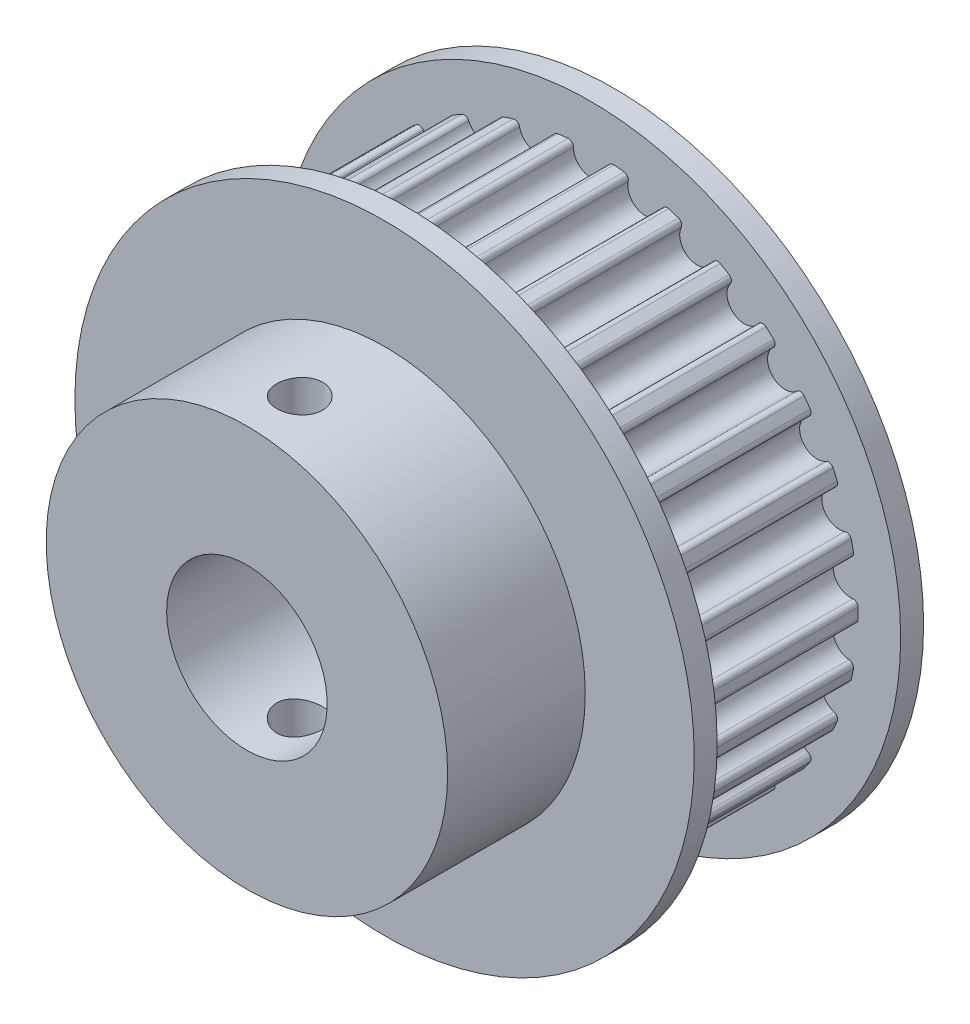
SolidWorks part; units mm, degrees
ref_plane "Front Plane" through (0, 0, 0) normal (0, 0, 1) x (1, 0, 0)
ref_plane "Top Plane" through (0, 0, 0) normal (0, 1, 0) x (1, 0, 0)
ref_plane "Right Plane" through (0, 0, 0) normal (1, 0, 0) x (0, 0, -1)
sketch "Sketch1" plane through (0, 0, 0) normal (0, 0, 1) x (1, 0, 0)
  line L0 (0, 0) -> (0, 28.7354) construction
  line L1 (0, 0) -> (41.8889, 0) construction
  line L2 (4.416, 20.7759) -> (6.2544, 29.4245) construction
  arc A2 (0, 21.24) -> (1.5249, 22.7816) centre (0, 22.765) ccw
  arc A4 (1.9916, 23.2147) -> (1.5249, 22.7816) centre (1.9549, 22.7863) ccw
  arc A5 (3.245, 22.6008) -> (4.416, 20.7759) centre (4.7331, 22.2675) ccw
  arc A6 (3.245, 22.6008) -> (2.8785, 23.1215) centre (2.8254, 22.6948) ccw
  arc A7 (2.8785, 23.1215) -> (1.9916, 23.2147) centre (0, 0) ccw
  arc A8 (4.416, 20.7759) -> (6.2282, 21.9667) centre (4.7331, 22.2675) ccw
  arc A9 (6.7747, 22.2933) -> (6.2282, 21.9667) centre (6.6497, 21.8819) ccw
  arc A10 (7.6228, 22.0178) -> (6.7747, 22.2933) centre (0, 0) ccw
  arc A11 (7.873, 21.4323) -> (7.6228, 22.0178) centre (7.4821, 21.6114) ccw
  arc A12 (7.873, 21.4323) -> (8.6391, 19.4037) centre (9.2594, 20.7969) ccw
  arc A13 (8.6391, 19.4037) -> (10.6592, 20.1918) centre (9.2594, 20.7969) ccw
  arc A14 (11.2617, 20.3976) -> (10.6592, 20.1918) centre (11.0539, 20.0212) ccw
  arc A15 (12.034, 19.9518) -> (11.2617, 20.3976) centre (0, 0) ccw
  arc A16 (12.157, 19.327) -> (12.034, 19.9518) centre (11.8119, 19.5836) ccw
  arc A17 (12.157, 19.327) -> (12.4846, 17.1835) centre (13.3809, 18.4173) ccw
  arc A18 (12.4846, 17.1835) -> (14.6244, 17.5344) centre (13.3809, 18.4173) ccw
  arc A19 (15.2565, 17.6104) -> (14.6244, 17.5344) centre (14.975, 17.2854) ccw
  arc A20 (15.9192, 17.0138) -> (15.2565, 17.6104) centre (0, 0) ccw
  arc A21 (15.9097, 16.3771) -> (15.9192, 17.0138) centre (15.6254, 16.6998) ccw
  arc A22 (15.9097, 16.3771) -> (15.7844, 14.2123) centre (16.9177, 15.2328) ccw
  arc A23 (15.7844, 14.2123) -> (17.9504, 14.1106) centre (16.9177, 15.2328) ccw
  arc A24 (18.5846, 14.0536) -> (17.9504, 14.1106) centre (18.2416, 13.7942) ccw
  arc A25 (19.1087, 13.3322) -> (18.5846, 14.0536) centre (0, 0) ccw
  arc A26 (18.967, 12.7114) -> (19.1087, 13.3322) centre (18.7561, 13.0861) ccw
  arc A27 (18.967, 12.7114) -> (18.3944, 10.62) centre (19.7151, 11.3825) ccw
  arc A28 (18.3944, 10.62) -> (20.4919, 10.0702) centre (19.7151, 11.3825) ccw
  arc A29 (21.1004, 9.8826) -> (20.4919, 10.0702) centre (20.711, 9.7002) ccw
  arc A30 (21.4631, 9.0679) -> (21.1004, 9.8826) centre (0, 0) ccw
  arc A31 (21.1954, 8.4902) -> (21.4631, 9.0679) centre (21.067, 8.9006) ccw
  arc A32 (21.1954, 8.4902) -> (20.2004, 6.5635) centre (21.6508, 7.0348) ccw
  arc A33 (20.2004, 6.5635) -> (22.1378, 5.5896) centre (21.6508, 7.0348) ccw
  arc A34 (22.694, 5.2796) -> (22.1378, 5.5896) centre (22.2751, 5.1821) ccw
  arc A35 (22.8794, 4.4073) -> (22.694, 5.2796) centre (0, 0) ccw
  arc A36 (22.4974, 3.8979) -> (22.8794, 4.4073) centre (22.4571, 4.326) ccw
  arc A37 (22.4974, 3.8979) -> (21.1236, 2.2202) centre (22.6403, 2.3796) ccw
  arc A38 (21.1236, 2.2202) -> (22.8162, 0.8648) centre (22.6403, 2.3796) ccw
  arc A39 (23.2957, 0.4459) -> (22.8162, 0.8648) centre (22.8658, 0.4376) ccw
  arc A40 (23.2957, -0.4459) -> (23.2957, 0.4459) centre (0, 0) ccw
  arc A41 (22.8162, -0.8648) -> (23.2957, -0.4459) centre (22.8658, -0.4376) ccw
  arc A42 (22.8162, -0.8648) -> (21.1236, -2.2202) centre (22.6403, -2.3796) ccw
  arc A43 (21.1236, -2.2202) -> (22.4974, -3.8979) centre (22.6403, -2.3796) ccw
  arc A44 (22.8794, -4.4073) -> (22.4974, -3.8979) centre (22.4571, -4.326) ccw
  arc A45 (22.694, -5.2796) -> (22.8794, -4.4073) centre (0, 0) ccw
  arc A46 (22.1378, -5.5896) -> (22.694, -5.2796) centre (22.2751, -5.1821) ccw
  arc A47 (22.1378, -5.5896) -> (20.2004, -6.5635) centre (21.6508, -7.0348) ccw
  arc A48 (20.2004, -6.5635) -> (21.1954, -8.4902) centre (21.6508, -7.0348) ccw
  arc A49 (21.4631, -9.0679) -> (21.1954, -8.4902) centre (21.067, -8.9006) ccw
  arc A50 (21.1004, -9.8826) -> (21.4631, -9.0679) centre (0, 0) ccw
  arc A51 (20.4919, -10.0702) -> (21.1004, -9.8826) centre (20.711, -9.7002) ccw
  arc A52 (20.4919, -10.0702) -> (18.3944, -10.62) centre (19.7151, -11.3825) ccw
  arc A53 (18.3944, -10.62) -> (18.967, -12.7114) centre (19.7151, -11.3825) ccw
  arc A54 (19.1087, -13.3322) -> (18.967, -12.7114) centre (18.7561, -13.0861) ccw
  arc A55 (18.5846, -14.0536) -> (19.1087, -13.3322) centre (0, 0) ccw
  arc A56 (17.9504, -14.1106) -> (18.5846, -14.0536) centre (18.2416, -13.7942) ccw
  arc A57 (17.9504, -14.1106) -> (15.7844, -14.2123) centre (16.9177, -15.2328) ccw
  arc A58 (15.7844, -14.2123) -> (15.9097, -16.3771) centre (16.9177, -15.2328) ccw
  arc A59 (15.9192, -17.0138) -> (15.9097, -16.3771) centre (15.6254, -16.6998) ccw
  arc A60 (15.2565, -17.6104) -> (15.9192, -17.0138) centre (0, 0) ccw
  arc A61 (14.6244, -17.5344) -> (15.2565, -17.6104) centre (14.975, -17.2854) ccw
  arc A62 (14.6244, -17.5344) -> (12.4846, -17.1835) centre (13.3809, -18.4173) ccw
  arc A63 (12.4846, -17.1835) -> (12.157, -19.327) centre (13.3809, -18.4173) ccw
  arc A64 (12.034, -19.9518) -> (12.157, -19.327) centre (11.8119, -19.5836) ccw
  arc A65 (11.2617, -20.3976) -> (12.034, -19.9518) centre (0, 0) ccw
  arc A66 (10.6592, -20.1918) -> (11.2617, -20.3976) centre (11.0539, -20.0212) ccw
  arc A67 (10.6592, -20.1918) -> (8.6391, -19.4037) centre (9.2594, -20.7969) ccw
  arc A68 (8.6391, -19.4037) -> (7.873, -21.4323) centre (9.2594, -20.7969) ccw
  arc A69 (7.6228, -22.0178) -> (7.873, -21.4323) centre (7.4821, -21.6114) ccw
  arc A70 (6.7747, -22.2933) -> (7.6228, -22.0178) centre (0, 0) ccw
  arc A71 (6.2282, -21.9667) -> (6.7747, -22.2933) centre (6.6497, -21.8819) ccw
  arc A72 (6.2282, -21.9667) -> (4.416, -20.7759) centre (4.7331, -22.2675) ccw
  arc A73 (4.416, -20.7759) -> (3.245, -22.6008) centre (4.7331, -22.2675) ccw
  arc A74 (2.8785, -23.1215) -> (3.245, -22.6008) centre (2.8254, -22.6948) ccw
  arc A75 (1.9916, -23.2147) -> (2.8785, -23.1215) centre (0, 0) ccw
  arc A76 (1.5249, -22.7816) -> (1.9916, -23.2147) centre (1.9549, -22.7863) ccw
  arc A77 (1.5249, -22.7816) -> (0, -21.24) centre (0, -22.765) ccw
  arc A78 (0, -21.24) -> (-1.5249, -22.7816) centre (0, -22.765) ccw
  arc A79 (-1.9916, -23.2147) -> (-1.5249, -22.7816) centre (-1.9549, -22.7863) ccw
  arc A80 (-2.8785, -23.1215) -> (-1.9916, -23.2147) centre (0, 0) ccw
  arc A81 (-3.245, -22.6008) -> (-2.8785, -23.1215) centre (-2.8254, -22.6948) ccw
  arc A82 (-3.245, -22.6008) -> (-4.416, -20.7759) centre (-4.7331, -22.2675) ccw
  arc A83 (-4.416, -20.7759) -> (-6.2282, -21.9667) centre (-4.7331, -22.2675) ccw
  arc A84 (-6.7747, -22.2933) -> (-6.2282, -21.9667) centre (-6.6497, -21.8819) ccw
  arc A85 (-7.6228, -22.0178) -> (-6.7747, -22.2933) centre (0, 0) ccw
  arc A86 (-7.873, -21.4323) -> (-7.6228, -22.0178) centre (-7.4821, -21.6114) ccw
  arc A87 (-7.873, -21.4323) -> (-8.6391, -19.4037) centre (-9.2594, -20.7969) ccw
  arc A88 (-8.6391, -19.4037) -> (-10.6592, -20.1918) centre (-9.2594, -20.7969) ccw
  arc A89 (-11.2617, -20.3976) -> (-10.6592, -20.1918) centre (-11.0539, -20.0212) ccw
  arc A90 (-12.034, -19.9518) -> (-11.2617, -20.3976) centre (0, 0) ccw
  arc A91 (-12.157, -19.327) -> (-12.034, -19.9518) centre (-11.8119, -19.5836) ccw
  arc A92 (-12.157, -19.327) -> (-12.4846, -17.1835) centre (-13.3809, -18.4173) ccw
  arc A93 (-12.4846, -17.1835) -> (-14.6244, -17.5344) centre (-13.3809, -18.4173) ccw
  arc A94 (-15.2565, -17.6104) -> (-14.6244, -17.5344) centre (-14.975, -17.2854) ccw
  arc A95 (-15.9192, -17.0138) -> (-15.2565, -17.6104) centre (0, 0) ccw
  arc A96 (-15.9097, -16.3771) -> (-15.9192, -17.0138) centre (-15.6254, -16.6998) ccw
  arc A97 (-15.9097, -16.3771) -> (-15.7844, -14.2123) centre (-16.9177, -15.2328) ccw
  arc A98 (-15.7844, -14.2123) -> (-17.9504, -14.1106) centre (-16.9177, -15.2328) ccw
  arc A99 (-18.5846, -14.0536) -> (-17.9504, -14.1106) centre (-18.2416, -13.7942) ccw
  arc A100 (-19.1087, -13.3322) -> (-18.5846, -14.0536) centre (0, 0) ccw
  arc A101 (-18.967, -12.7114) -> (-19.1087, -13.3322) centre (-18.7561, -13.0861) ccw
  arc A102 (-18.967, -12.7114) -> (-18.3944, -10.62) centre (-19.7151, -11.3825) ccw
  arc A103 (-18.3944, -10.62) -> (-20.4919, -10.0702) centre (-19.7151, -11.3825) ccw
  arc A104 (-21.1004, -9.8826) -> (-20.4919, -10.0702) centre (-20.711, -9.7002) ccw
  arc A105 (-21.4631, -9.0679) -> (-21.1004, -9.8826) centre (0, 0) ccw
  arc A106 (-21.1954, -8.4902) -> (-21.4631, -9.0679) centre (-21.067, -8.9006) ccw
  arc A107 (-21.1954, -8.4902) -> (-20.2004, -6.5635) centre (-21.6508, -7.0348) ccw
  arc A108 (-20.2004, -6.5635) -> (-22.1378, -5.5896) centre (-21.6508, -7.0348) ccw
  arc A109 (-22.694, -5.2796) -> (-22.1378, -5.5896) centre (-22.2751, -5.1821) ccw
  arc A110 (-22.8794, -4.4073) -> (-22.694, -5.2796) centre (0, 0) ccw
  arc A111 (-22.4974, -3.8979) -> (-22.8794, -4.4073) centre (-22.4571, -4.326) ccw
  arc A112 (-22.4974, -3.8979) -> (-21.1236, -2.2202) centre (-22.6403, -2.3796) ccw
  arc A113 (-21.1236, -2.2202) -> (-22.8162, -0.8648) centre (-22.6403, -2.3796) ccw
  arc A114 (-23.2957, -0.4459) -> (-22.8162, -0.8648) centre (-22.8658, -0.4376) ccw
  arc A115 (-23.2957, 0.4459) -> (-23.2957, -0.4459) centre (0, 0) ccw
  arc A116 (-22.8162, 0.8648) -> (-23.2957, 0.4459) centre (-22.8658, 0.4376) ccw
  arc A117 (-22.8162, 0.8648) -> (-21.1236, 2.2202) centre (-22.6403, 2.3796) ccw
  arc A118 (-21.1236, 2.2202) -> (-22.4974, 3.8979) centre (-22.6403, 2.3796) ccw
  arc A119 (-22.8794, 4.4073) -> (-22.4974, 3.8979) centre (-22.4571, 4.326) ccw
  arc A120 (-22.694, 5.2796) -> (-22.8794, 4.4073) centre (0, 0) ccw
  arc A121 (-22.1378, 5.5896) -> (-22.694, 5.2796) centre (-22.2751, 5.1821) ccw
  arc A122 (-22.1378, 5.5896) -> (-20.2004, 6.5635) centre (-21.6508, 7.0348) ccw
  arc A123 (-20.2004, 6.5635) -> (-21.1954, 8.4902) centre (-21.6508, 7.0348) ccw
  arc A124 (-21.4631, 9.0679) -> (-21.1954, 8.4902) centre (-21.067, 8.9006) ccw
  arc A125 (-21.1004, 9.8826) -> (-21.4631, 9.0679) centre (0, 0) ccw
  arc A126 (-20.4919, 10.0702) -> (-21.1004, 9.8826) centre (-20.711, 9.7002) ccw
  arc A127 (-20.4919, 10.0702) -> (-18.3944, 10.62) centre (-19.7151, 11.3825) ccw
  arc A128 (-18.3944, 10.62) -> (-18.967, 12.7114) centre (-19.7151, 11.3825) ccw
  arc A129 (-19.1087, 13.3322) -> (-18.967, 12.7114) centre (-18.7561, 13.0861) ccw
  arc A130 (-18.5846, 14.0536) -> (-19.1087, 13.3322) centre (0, 0) ccw
  arc A131 (-17.9504, 14.1106) -> (-18.5846, 14.0536) centre (-18.2416, 13.7942) ccw
  arc A132 (-17.9504, 14.1106) -> (-15.7844, 14.2123) centre (-16.9177, 15.2328) ccw
  arc A133 (-15.7844, 14.2123) -> (-15.9097, 16.3771) centre (-16.9177, 15.2328) ccw
  arc A134 (-15.9192, 17.0138) -> (-15.9097, 16.3771) centre (-15.6254, 16.6998) ccw
  arc A135 (-15.2565, 17.6104) -> (-15.9192, 17.0138) centre (0, 0) ccw
  arc A136 (-14.6244, 17.5344) -> (-15.2565, 17.6104) centre (-14.975, 17.2854) ccw
  arc A137 (-14.6244, 17.5344) -> (-12.4846, 17.1835) centre (-13.3809, 18.4173) ccw
  arc A138 (-12.4846, 17.1835) -> (-12.157, 19.327) centre (-13.3809, 18.4173) ccw
  arc A139 (-12.034, 19.9518) -> (-12.157, 19.327) centre (-11.8119, 19.5836) ccw
  arc A140 (-11.2617, 20.3976) -> (-12.034, 19.9518) centre (0, 0) ccw
  arc A141 (-10.6592, 20.1918) -> (-11.2617, 20.3976) centre (-11.0539, 20.0212) ccw
  arc A142 (-10.6592, 20.1918) -> (-8.6391, 19.4037) centre (-9.2594, 20.7969) ccw
  arc A143 (-8.6391, 19.4037) -> (-7.873, 21.4323) centre (-9.2594, 20.7969) ccw
  arc A144 (-7.6228, 22.0178) -> (-7.873, 21.4323) centre (-7.4821, 21.6114) ccw
  arc A145 (-6.7747, 22.2933) -> (-7.6228, 22.0178) centre (0, 0) ccw
  arc A146 (-6.2282, 21.9667) -> (-6.7747, 22.2933) centre (-6.6497, 21.8819) ccw
  arc A147 (-6.2282, 21.9667) -> (-4.416, 20.7759) centre (-4.7331, 22.2675) ccw
  arc A148 (-4.416, 20.7759) -> (-3.245, 22.6008) centre (-4.7331, 22.2675) ccw
  arc A149 (-2.8785, 23.1215) -> (-3.245, 22.6008) centre (-2.8254, 22.6948) ccw
  arc A150 (-1.9916, 23.2147) -> (-2.8785, 23.1215) centre (0, 0) ccw
  arc A151 (-1.5249, 22.7816) -> (-1.9916, 23.2147) centre (-1.9549, 22.7863) ccw
  arc A152 (-1.5249, 22.7816) -> (0, 21.24) centre (0, 22.765) ccw
  arc A153 (21.1236, -2.2202) -> (21.24, 0) centre (0, 0) ccw
  point P309 (0, 0)
  dimension "D1" = 30
  dimension "D3" = 3.05
  dimension "D4" = 0.86
  dimension "D6" = 3.05
  dimension "D7" = 0.86
extrude "Boss-Extrude1" add sketch "Sketch1" along normal blind 16 contours A43 A44 A45 A46 A47 A48 A49 A50 A51 A52 A53 A54 A55 A56 A57 A58 A59 A60 A61 A62 A63 A64 A65 A66 A67 A68 A69 A70 A71 A72 A73 A74 A75 A76 A77 A78 A79 A80 A81 A82 A83 A84 A85 A86 A87 A88 A89 A90 A91 A92 A93 A94 A95 A96 A97 A98 A99 A100 A101 A102 A103 A104 A105 A106 A107 A108 A109 A110 A111 A112 A113 A114 A115 A116 A117 A118 A119 A120 A121 A122 A123 A124 A125 A126 A127 A128 A129 A130 A131 A132 A133 A134 A135 A136 A137 A138 A139 A140 A141 A142 A143 A144 A145 A146 A147 A148 A149 A150 A151 A152 A2 A4 A7 A6 A5 A8 A9 A10 A11 A12 A13 A14 A15 A16 A17 A18 A19 A20 A21 A22 A23 A24 A25 A26 A27 A28 A29 A30 A31 A32 A33 A34 A35 A36 A37 A38 A39 A40 A41 A42
sketch "Sketch2" plane through (0, 0, 16) normal (0, 0, 1) x (1, 0, 0)
  circle A0 centre (0, 0) radius 27
  dimension "D1" = 54
extrude "Boss-Extrude2" add sketch "Sketch2" along normal blind 2
ref_plane "Plane2" through (0, 0, 8) normal (0, 0, -1) x (-1, 0, 0)
mirror "Mirror2" about plane through (0, 0, 8) normal (0, 0, -1) of "Boss-Extrude2"
sketch "Sketch4" plane through (0, 0, 18) normal (0, 0, 1) x (1, 0, 0)
  circle A0 centre (0, 0) radius 17.5
  dimension "D1" = 35
extrude "Boss-Extrude3" add sketch "Sketch4" along normal blind 12
sketch "Sketch5" plane through (0, 0, -2) normal (0, 0, -1) x (-1, 0, 0)
  circle A0 centre (0, 0) radius 7
  dimension "D1" = 14
extrude "Cut-Extrude2" cut sketch "Sketch5" against normal through all
sketch "Sketch6" plane through (0, 0, 0) normal (0, 1, 0) x (1, 0, 0)
  line L0 (-17.5, -30) -> (17.5, -30) construction
  circle A0 centre (0, -25.4) radius 2
  dimension "D2" = 4
  dimension "D1" = 4.6
extrude "Cut-Extrude3" cut sketch "Sketch6" against normal through all both and the other way through all
sketch "Sketch7" plane through (0, 0, 30) normal (0, 0, 1) x (1, 0, 0)
  line L0 (-7, 0) -> (42.3342, 0) construction
  circle A0 centre (0, 0) radius 7 construction
